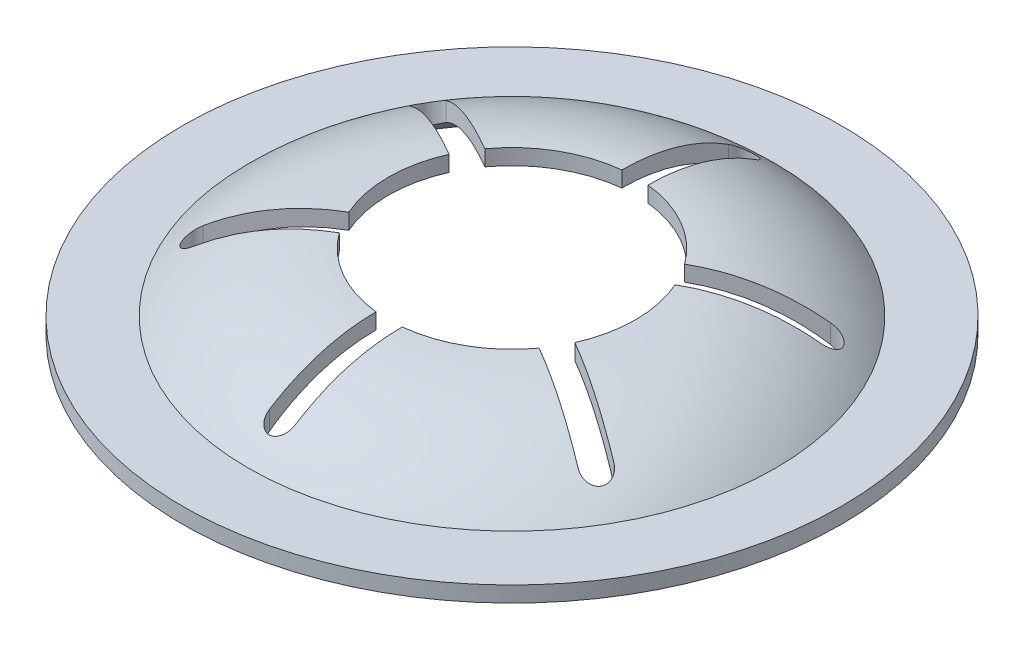
SolidWorks part; units mm, degrees
ref_plane "Front Plane" through (0, 0, 0) normal (0, 0, 1) x (1, 0, 0)
ref_plane "Top Plane" through (0, 0, 0) normal (0, 1, 0) x (1, 0, 0)
ref_plane "Right Plane" through (0, 0, 0) normal (1, 0, 0) x (0, 0, -1)
sketch "Sketch2" plane through (0, 0, 0) normal (0, 0, 1) x (1, 0, 0)
  line L0 (0, 0) -> (0, 1.8) construction
  line L1 (-8, 0) -> (-6.2371, 0)
  line L2 (-3, 1.8) -> (-3, 1.419)
  line L3 (-8, 0) -> (-8, 0.381)
  line L4 (-8, 0.381) -> (-6.4, 0.381)
  line L5 (0, 1.8) -> (-3, 1.8) construction
  arc A0 (-6.2371, 0) -> (-3, 1.419) centre (-3, -2.9828) cw
  arc A1 (-6.4, 0.381) -> (-3, 1.8) centre (-3, -2.9828) cw
  dimension "Ht" = 1.8
  dimension "OD" = 16
  dimension "D3" = 0.381
  dimension "D4" = 12.8
  dimension "Shaft Dia" = 6
revolve "Revolve1" add sketch "Sketch2" angle 360 about L0
sketch "Sketch3" plane through (0, 0, 0) normal (0, 1, 0) x (1, 0, 0)
  line L1 (-0.3175, 5.5745) -> (0.3175, 5.5745) construction
  line L2 (-0.3175, 5.5745) -> (-0.3175, 0)
  line L3 (-0.3175, 0) -> (0.3175, 0)
  line L4 (0.3175, 5.5745) -> (0.3175, 0)
  arc A0 (-0.3175, 5.5745) -> (0.3175, 5.5745) centre (0, 5.5745) cw
  circle A4 centre (0, 0) radius 5.892
  circle A5 centre (0, 0) radius 5.892 construction
  dimension "D2" = 0.635
  dimension "D1" = 0.508
extrude "Cut-Extrude1" cut sketch "Sketch3" along normal through all
pattern_circular "CirPattern1" count 6 over 360 about axis through (0, 0, 0) along (0, 1, 0) of "Cut-Extrude1"
equation "\"D4@Sketch2\" = \"OD@Sketch2\"*.8"
